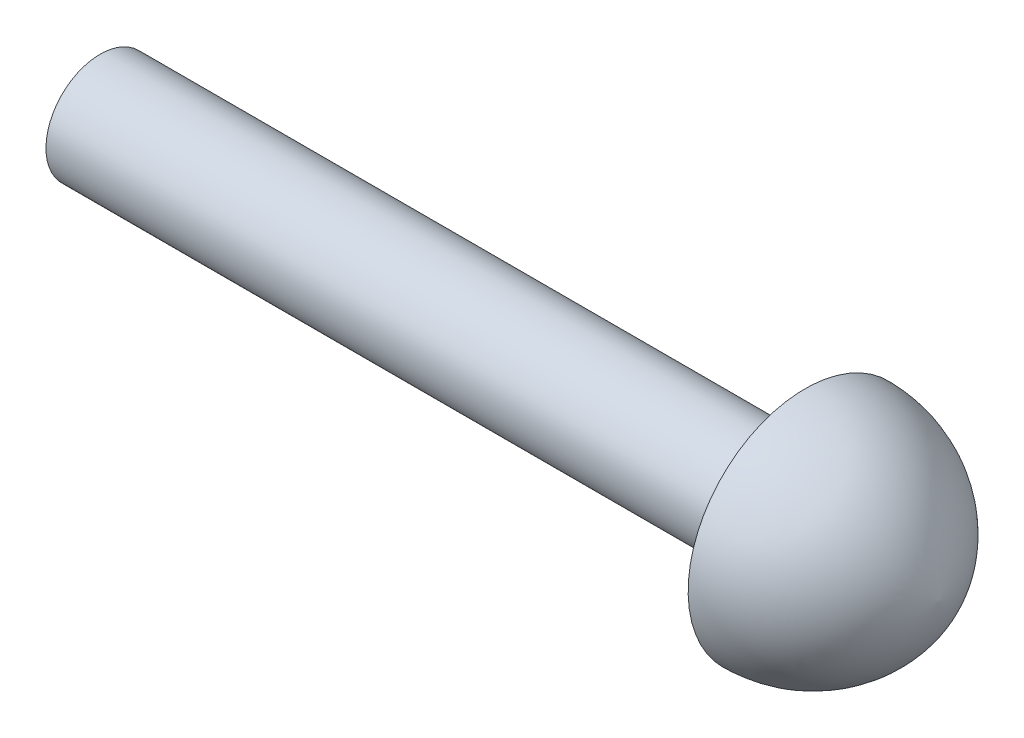
SolidWorks part; units mm, degrees
ref_plane "Front Plane" through (0, 0, 0) normal (0, 0, 1) x (1, 0, 0)
ref_plane "Top Plane" through (0, 0, 0) normal (0, 1, 0) x (1, 0, 0)
ref_plane "Right Plane" through (0, 0, 0) normal (1, 0, 0) x (0, 0, -1)
sketch "Sketch1" plane through (0, 0, 0) normal (0, 0, 1) x (1, 0, 0)
  line L0 (0, 0) -> (0, 2)
  line L1 (0, 2) -> (26, 2)
  line L2 (26, 2) -> (26, 4.3119)
  line L3 (0, 0) -> (30.9524, 0)
  arc A0 (26, 4.3119) -> (30.9524, 0) centre (26, -0.6881) cw
  dimension "D3" = 5
  dimension "D1" = 2
  dimension "D2" = 26
revolve "Revolve1" add sketch "Sketch1" angle 360 about L3
